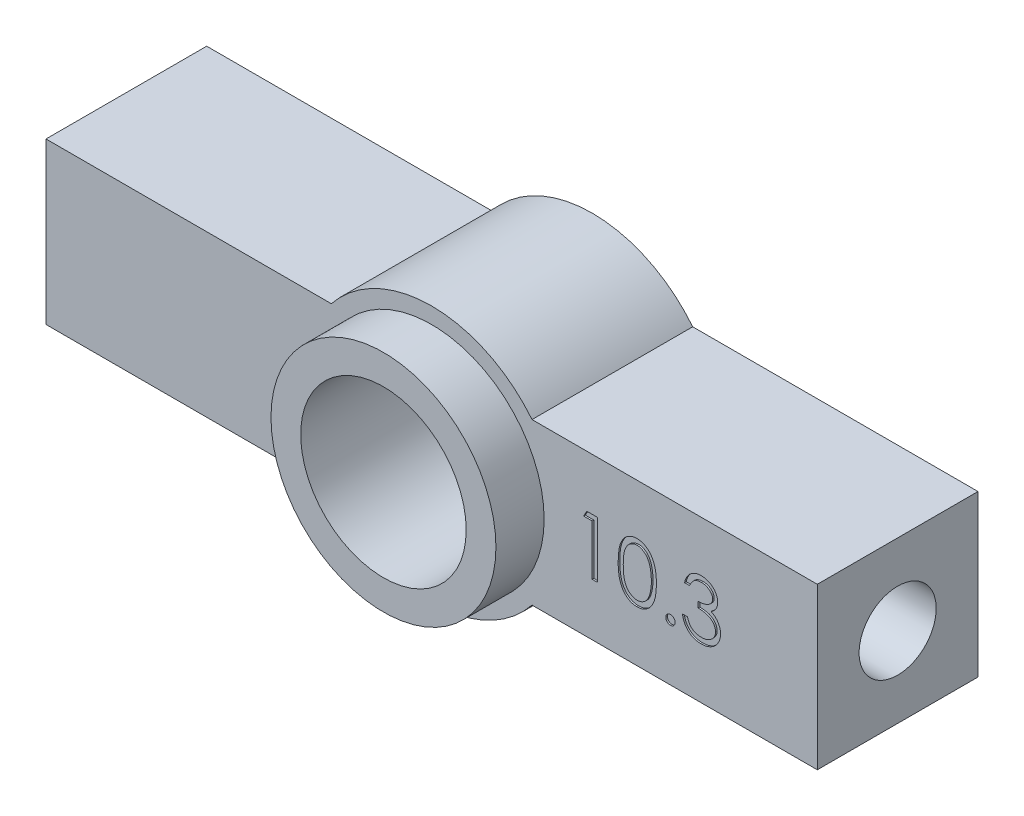
SolidWorks part; units mm, degrees
ref_plane "正面" through (0, 0, 0) normal (0, 0, 1) x (1, 0, 0)
ref_plane "平面" through (0, 0, 0) normal (0, 1, 0) x (1, 0, 0)
ref_plane "右側面" through (0, 0, 0) normal (1, 0, 0) x (0, 0, -1)
sketch "ｽｹｯﾁ1" plane through (0, 0, 0) normal (0, 0, 1) x (1, 0, 0)
  line L0 (-6.245, 5) -> (-24, 5)
  line L2 (-24, 5) -> (-24, -5)
  line L4 (24, 5) -> (24, -5)
  line L5 (-24, 5) -> (24, -5) construction
  line L6 (-24, -5) -> (24, 5) construction
  line L7 (6.245, 5) -> (24, 5)
  line L8 (-6.245, -5) -> (-24, -5)
  line L9 (6.245, -5) -> (24, -5)
  circle A0 centre (0, 0) radius 5.15
  arc A1 (6.245, 5) -> (-6.245, 5) centre (0, 0) ccw
  arc A2 (6.245, -5) -> (-6.245, -5) centre (0, 0) cw
  dimension "D1" = 10.3
  dimension "D4" = 8
  dimension "D2" = 10
  dimension "D3" = 48
extrude "ﾎﾞｽ - 押し出し1" add sketch "ｽｹｯﾁ1" along normal blind 10
sketch "ｽｹｯﾁ3" plane through (24, 0, 0) normal (1, 0, 0) x (0, 0, -1)
  circle A0 centre (-5, 0) radius 2.4
  dimension "D1" = 4.8
extrude "ｶｯﾄ - 押し出し1" cut sketch "ｽｹｯﾁ3" against normal blind 6
sketch "ｽｹｯﾁ4" plane through (-24, 0, 0) normal (-1, 0, 0) x (0, 0, 1)
  circle A0 centre (5, 0) radius 2.4
  dimension "D1" = 4.8
extrude "ｶｯﾄ - 押し出し2" cut sketch "ｽｹｯﾁ4" against normal blind 6
sketch "ｽｹｯﾁ7" plane through (0, 0, 10) normal (0, 0, 1) x (1, 0, 0)
  text T0 "10.3"
extrude "ｶｯﾄ - 押し出し4" cut sketch "ｽｹｯﾁ7" against normal blind 0.1
sketch "ｽｹｯﾁ8" plane through (0, 0, 10) normal (0, 0, 1) x (1, 0, 0)
  circle A0 centre (0, 0) radius 5.15
  circle A1 centre (0, 0) radius 7
  dimension "D1" = 14
extrude "ﾎﾞｽ - 押し出し2" add sketch "ｽｹｯﾁ8" along normal blind 3
